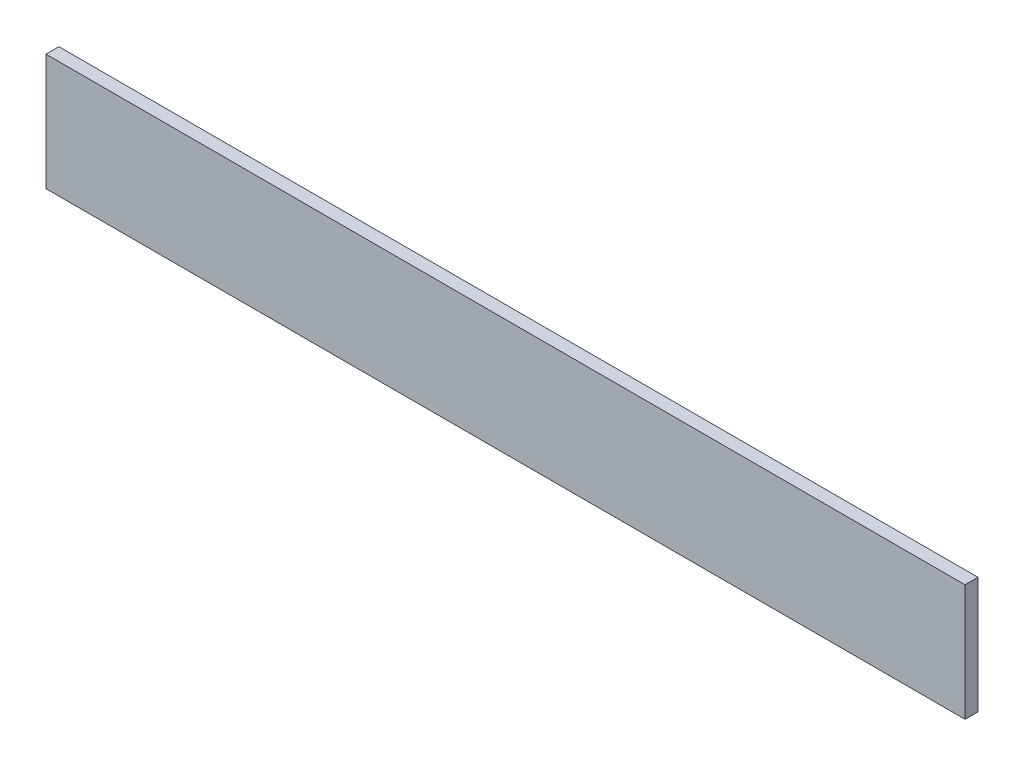
SolidWorks part; units mm, degrees
ref_plane "Front Plane" through (0, 0, 0) normal (0, 0, 1) x (1, 0, 0)
ref_plane "Top Plane" through (0, 0, 0) normal (0, 1, 0) x (1, 0, 0)
ref_plane "Right Plane" through (0, 0, 0) normal (1, 0, 0) x (0, 0, -1)
sketch "Sketch1" plane through (0, 0, 0) normal (0, 0, 1) x (1, 0, 0)
  line L1 (0, 0) -> (901.7, 0)
  line L2 (0, 0) -> (0, 114.3)
  line L3 (0, 114.3) -> (901.7, 114.3)
  line L4 (901.7, 0) -> (901.7, 114.3)
  dimension "D1" = 901.7
  dimension "D2" = 114.3
extrude "Boss-Extrude1" add sketch "Sketch1" along normal blind 12.7
